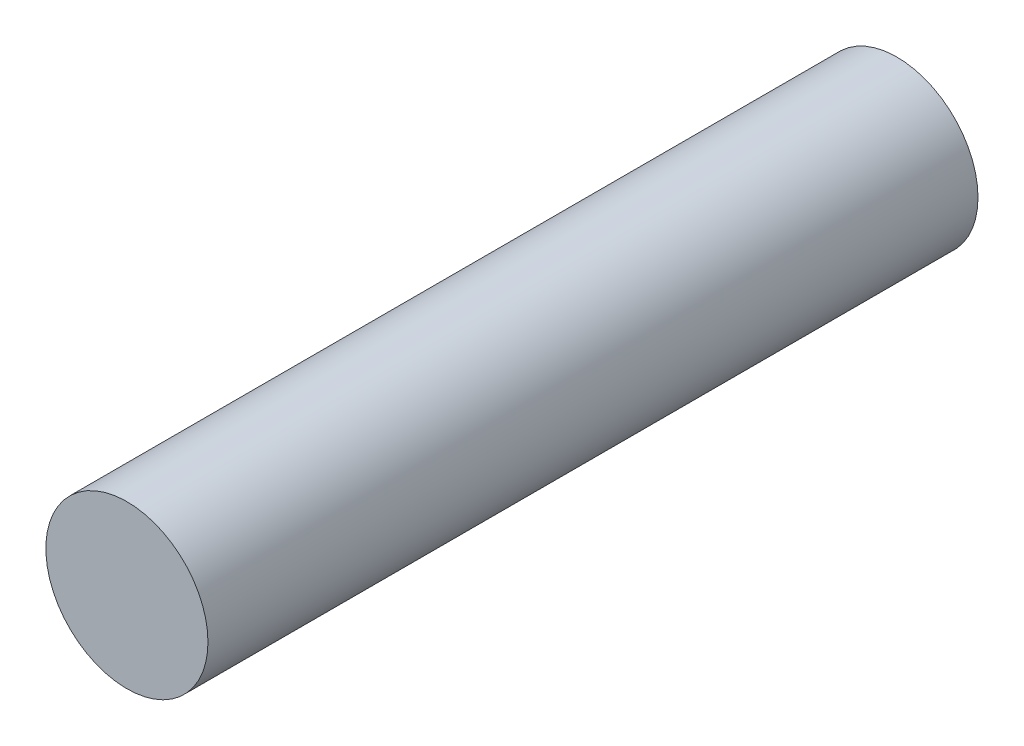
SolidWorks part; units mm, degrees
ref_plane "前视基准面" through (0, 0, 0) normal (0, 0, 1) x (1, 0, 0)
ref_plane "上视基准面" through (0, 0, 0) normal (0, 1, 0) x (1, 0, 0)
ref_plane "右视基准面" through (0, 0, 0) normal (1, 0, 0) x (0, 0, -1)
other "Configuration Table"
sketch "草图1" plane through (0, 0, 0) normal (0, 0, 1) x (1, 0, 0)
  circle A0 centre (0, 0) radius 2
  dimension "diameter" = 4
extrude "Driver_power_cable_envelope" add sketch "草图1" along normal blind 19
